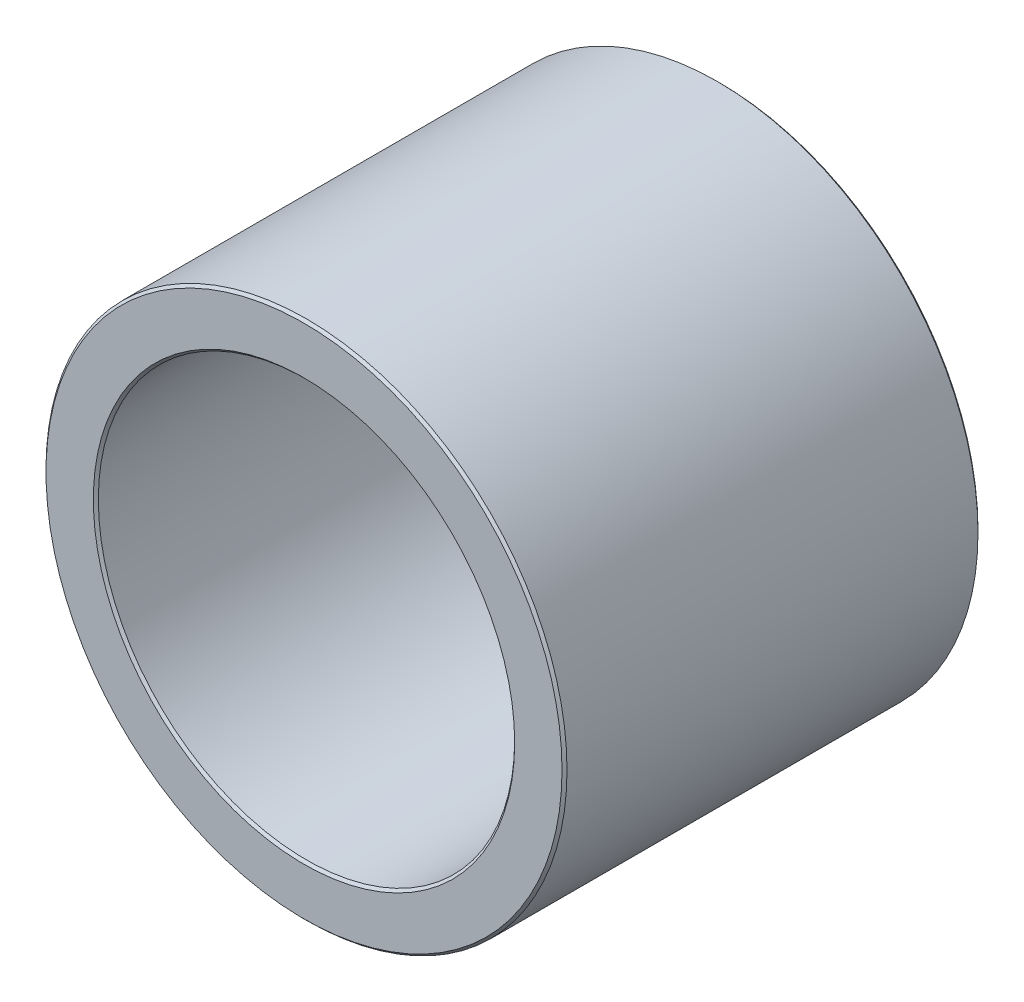
SolidWorks part; units mm, degrees
ref_plane "Front Plane" through (0, 0, 0) normal (0, 0, 1) x (1, 0, 0)
ref_plane "Top Plane" through (0, 0, 0) normal (0, 1, 0) x (1, 0, 0)
ref_plane "Right Plane" through (0, 0, 0) normal (1, 0, 0) x (0, 0, -1)
sketch "Sketch1" plane through (0, 0, 0) normal (0, 0, 1) x (1, 0, 0)
  circle A0 centre (0, 0) radius 7.515
  circle A1 centre (0, 0) radius 6.005
  point P8 (0, -7.515)
  point P9 (0, 7.515)
  dimension "ID" = 12.01
  dimension "OD" = 15.03
sketch "Sketch2" plane through (0, 0, 0) normal (1, 0, 0) x (0, 0, -1)
  line L0 (6, 0) -> (-6, 0) construction
  line L1 (6, 7.515) -> (-6, 7.515) construction
  point P4 (0, 0)
  point P8 (0, 7.515)
  point P9 (0, 7.515)
  dimension "Length" = 12
sketch "Sketch5" plane through (0, 0, 0) normal (0, 0, 1) x (1, 0, 0)
  circle A0 centre (0, 0) radius 6.005 construction
  circle A1 centre (0, 0) radius 7.515 construction
  circle A2 centre (0, 0) radius 6.005
  circle A3 centre (0, 0) radius 7.515
extrude "Boss-Extrude1" add sketch "Sketch5" along normal up to vertex (6 mm away) and the other way up to vertex (6 mm away) up to point (0, 0, 6) other way up to point (0, 0, -6)
chamfer "Chamfer1" distance 0.0721 angle 45 4 edges at (7.515, 0, -6) (6.005, 0, -6) (6.005, 0, 6) (7.515, 0, 6)
equation "\"D1@Chamfer1\"=\"ID@Sketch1\"*.006"
